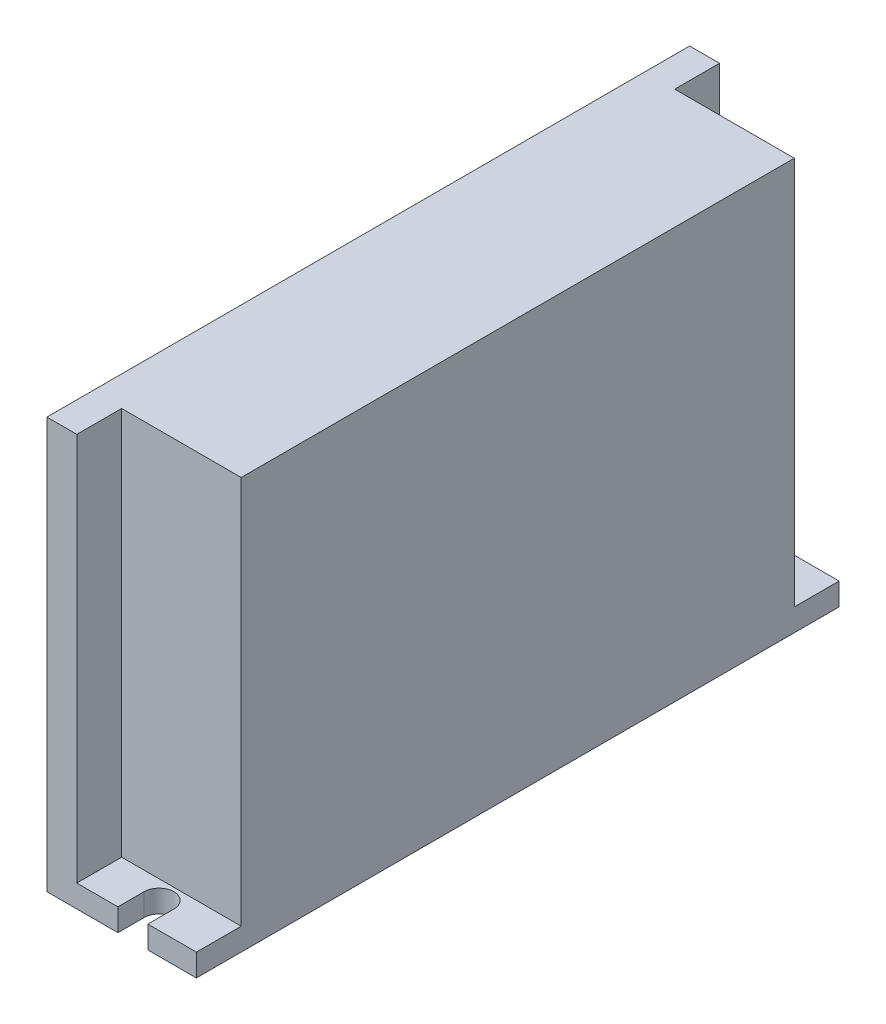
SolidWorks part; units mm, degrees
ref_plane "Front Plane" through (0, 0, 0) normal (0, 0, 1) x (1, 0, 0)
ref_plane "Top Plane" through (0, 0, 0) normal (0, 1, 0) x (1, 0, 0)
ref_plane "Right Plane" through (0, 0, 0) normal (1, 0, 0) x (0, 0, -1)
sketch "Sketch1" plane through (0, 0, 0) normal (0, 1, 0) x (1, 0, 0)
  line L1 (-10, -43) -> (10, -43)
  line L2 (-10, -43) -> (-10, 43)
  line L3 (-10, 43) -> (10, 43)
  line L4 (10, -43) -> (10, 43)
  line L5 (-10, -43) -> (10, 43) construction
  line L6 (-10, 43) -> (10, -43) construction
  point P0 (0, 0)
  dimension "D1" = 20
  dimension "D2" = 86
extrude "Boss-Extrude1" add sketch "Sketch1" along normal blind 3
sketch "Sketch2" plane through (0, 3, 0) normal (0, 1, 0) x (1, 0, 0)
  line L0 (10, 0) -> (-10, 0) construction
  line L1 (10, -43) -> (10, 43) construction
  line L2 (-10, 43) -> (-10, -43) construction
  line L3 (-0.5, 39.5) -> (-0.5, 43)
  line L4 (10, 43) -> (-10, 43) construction
  line L5 (3.5, 39.5) -> (3.5, 43)
  line L6 (-0.5, -39.5) -> (-0.5, -43)
  line L7 (-10, -43) -> (10, -43) construction
  line L8 (3.5, -39.5) -> (3.5, -43)
  line L9 (3.5, 43) -> (-0.5, 43)
  line L10 (3.5, -43) -> (-0.5, -43)
  arc A0 (-0.5, 39.5) -> (3.5, 39.5) centre (1.5, 39.5) ccw
  arc A1 (3.5, -39.5) -> (-0.5, -39.5) centre (1.5, -39.5) ccw
  dimension "D1" = 4
  dimension "D2" = 79
  dimension "D3" = 11.5
extrude "Cut-Extrude1" cut sketch "Sketch2" against normal through all
sketch "Sketch3" plane through (0, 3, 0) normal (0, 1, 0) x (1, 0, 0)
  line L0 (-10, -43) -> (-0.5, -43) construction
  line L1 (-10, 43) -> (-6, 43)
  line L2 (-10, 43) -> (-10, -43)
  line L3 (-10, -43) -> (-6, -43)
  line L4 (-6, 43) -> (-6, -43)
  dimension "D1" = 4
extrude "Boss-Extrude2" add sketch "Sketch3" along normal blind 52
sketch "Sketch4" plane through (0, 3, 0) normal (0, 1, 0) x (1, 0, 0)
  line L0 (10, -43) -> (10, 43) construction
  line L1 (10, 37) -> (-6, 37)
  line L2 (10, 37) -> (10, -37)
  line L3 (10, -37) -> (-6, -37)
  line L4 (-6, 37) -> (-6, -37)
  line L5 (-6, -43) -> (-6, 43) construction
  line L6 (10, 0) -> (-6, 0) construction
  line L7 (10, 43) -> (3.5, 43) construction
  dimension "D1" = 6
extrude "Boss-Extrude3" add sketch "Sketch4" along normal blind 52
